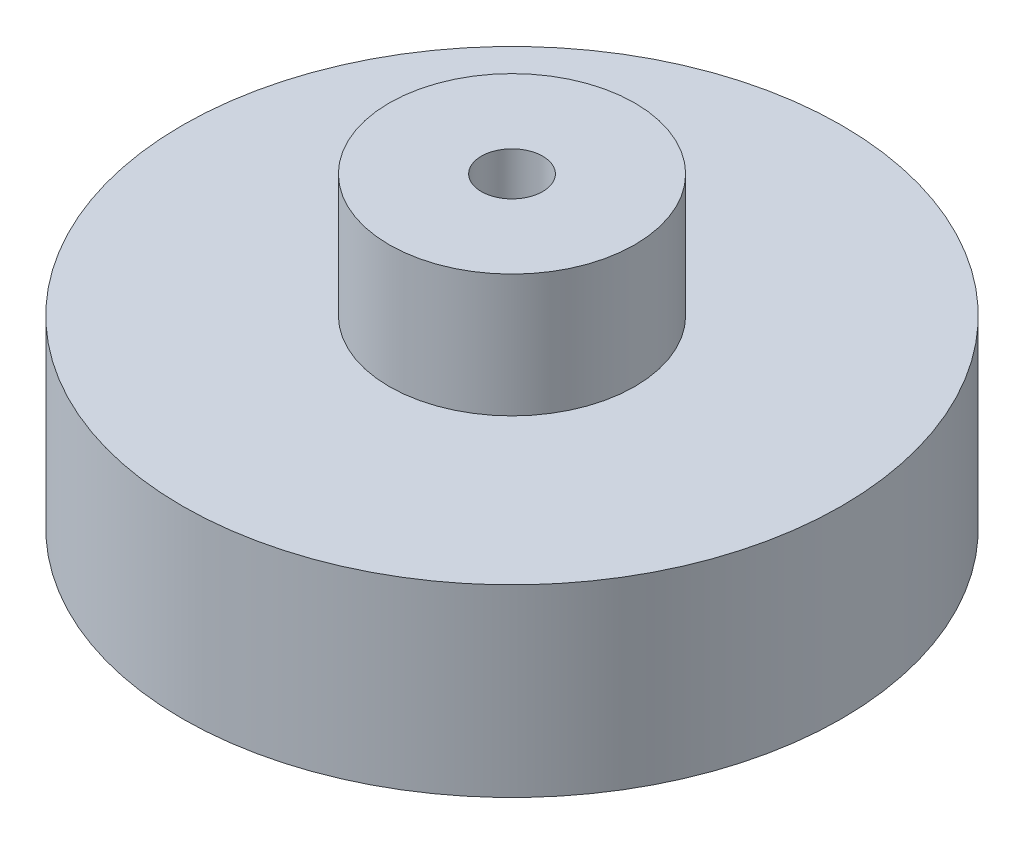
SolidWorks part; units mm, degrees
ref_plane "정면" through (0, 0, 0) normal (0, 0, 1) x (1, 0, 0)
ref_plane "윗면" through (0, 0, 0) normal (0, 1, 0) x (1, 0, 0)
ref_plane "우측면" through (0, 0, 0) normal (1, 0, 0) x (0, 0, -1)
sketch "스케치1" plane through (0, 0, 0) normal (0, 1, 0) x (1, 0, 0)
  circle A0 centre (0, 0) radius 26.85
  dimension "D1" = 53.7
extrude "보스-돌출1" add sketch "스케치1" along normal blind 15
sketch "스케치3" plane through (0, 15, 0) normal (0, 1, 0) x (1, 0, 0)
  circle A0 centre (0, 0) radius 10
extrude "보스-돌출2" add sketch "스케치3" along normal blind 10
sketch "스케치2" plane through (0, 0, 0) normal (0, -1, 0) x (1, 0, 0)
  circle A0 centre (0, 0) radius 2.5
  dimension "D1" = 5
extrude "컷-돌출1" cut sketch "스케치2" against normal through all
